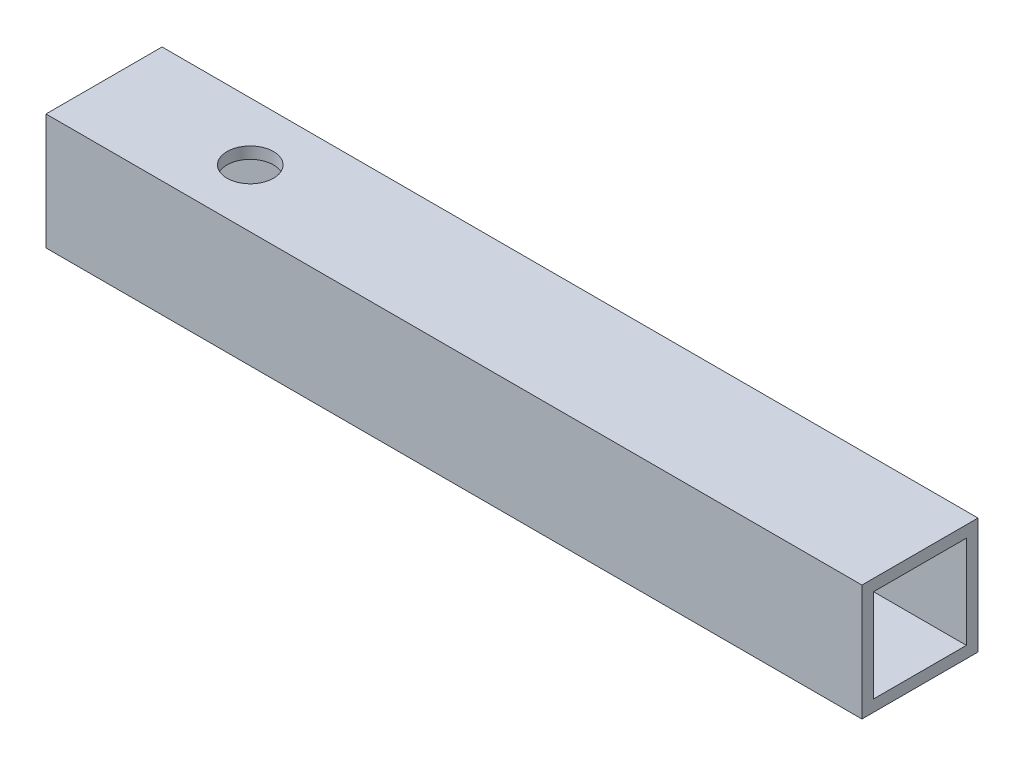
SolidWorks part; units mm, degrees
material "Brass"
ref_plane "Front Plane" through (0, 0, 0) normal (0, 0, 1) x (1, 0, 0)
ref_plane "Top Plane" through (0, 0, 0) normal (0, 1, 0) x (1, 0, 0)
ref_plane "Right Plane" through (0, 0, 0) normal (1, 0, 0) x (0, 0, -1)
sketch "Sketch2" plane through (0, 0, 0) normal (1, 0, 0) x (0, 0, -1)
  line L1 (-1.9844, 1.9844) -> (1.9844, 1.9844)
  line L2 (-1.9844, 1.9844) -> (-1.9844, -1.9844)
  line L3 (-1.9844, -1.9844) -> (1.9844, -1.9844)
  line L4 (1.9844, 1.9844) -> (1.9844, -1.9844)
  line L5 (-1.9844, 1.9844) -> (1.9844, -1.9844) construction
  line L6 (-1.9844, -1.9844) -> (1.9844, 1.9844) construction
  point P0 (0, 0)
  dimension "D1" = 3.9688
  dimension "D2" = 3.9688
extrude "Boss-Extrude1" add sketch "Sketch2" along normal blind 27.9
sketch "Sketch3" plane through (0, 0, 0) normal (-1, 0, 0) x (0, 0, 1)
  line L1 (-1.5875, 1.5875) -> (1.5875, 1.5875)
  line L2 (-1.5875, 1.5875) -> (-1.5875, -1.5875)
  line L3 (-1.5875, -1.5875) -> (1.5875, -1.5875)
  line L4 (1.5875, 1.5875) -> (1.5875, -1.5875)
  line L5 (-1.5875, 1.5875) -> (1.5875, -1.5875) construction
  line L6 (-1.5875, -1.5875) -> (1.5875, 1.5875) construction
  point P0 (0, 0)
  dimension "D1" = 3.175
  dimension "D2" = 3.175
extrude "Cut-Extrude1" cut sketch "Sketch3" against normal through all
sketch "Sketch4" plane through (0, 1.9844, 0) normal (0, 1, 0) x (1, 0, 0)
  line L0 (0, 1.9844) -> (0, -1.9844) construction
  circle A0 centre (5, 0) radius 0.7938
  dimension "D2" = 1.5875
  dimension "D1" = 5
extrude "Cut-Extrude2" cut sketch "Sketch4" against normal blind 10
